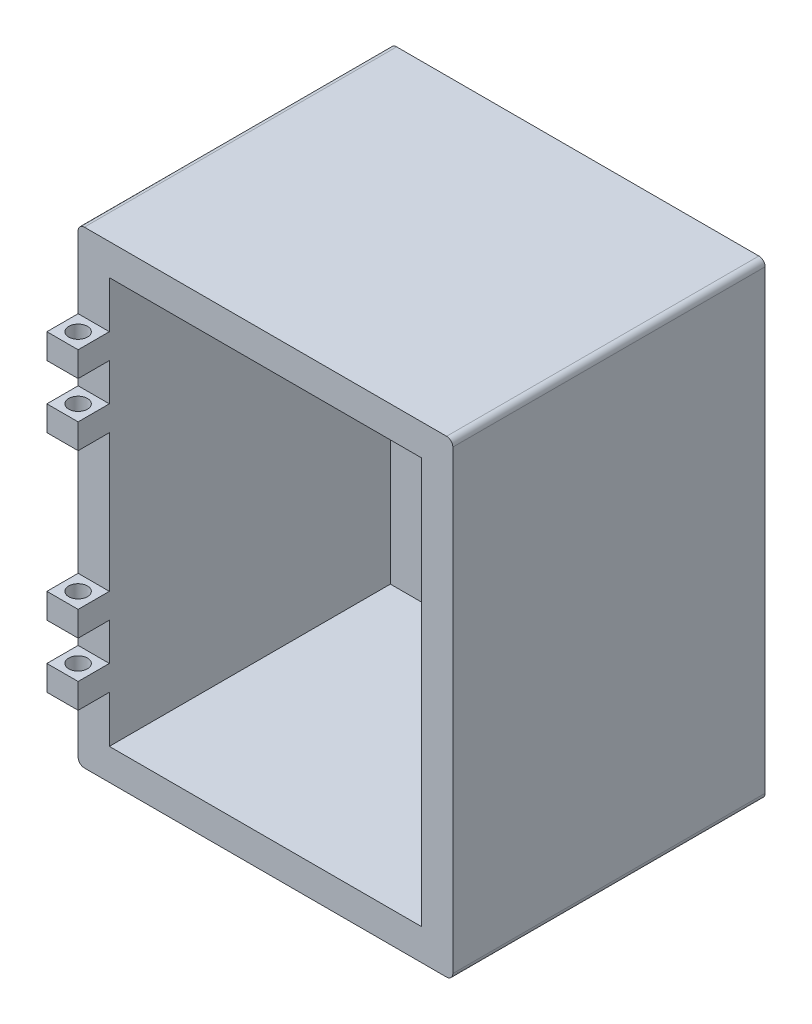
SolidWorks part; units mm, degrees
ref_plane "Front Plane" through (0, 0, 0) normal (0, 0, 1) x (1, 0, 0)
ref_plane "Top Plane" through (0, 0, 0) normal (0, 1, 0) x (1, 0, 0)
ref_plane "Right Plane" through (0, 0, 0) normal (1, 0, 0) x (0, 0, -1)
sketch "Sketch1" plane through (0, 0, 0) normal (0, 0, 1) x (1, 0, 0)
  line L1 (0, 0) -> (120, 0)
  line L2 (0, 0) -> (0, 150)
  line L3 (0, 150) -> (120, 150)
  line L4 (120, 0) -> (120, 150)
  dimension "D1" = 120
  dimension "D2" = 150
extrude "Boss-Extrude1" add sketch "Sketch1" along normal blind 100
shell "Shell1" thickness 10
sketch "Sketch2" plane through (0, 0, 100) normal (0, 0, 1) x (1, 0, 0)
  line L0 (0, 150) -> (0, 0) construction
  line L1 (0, 97) -> (10, 97)
  line L2 (0, 97) -> (0, 105)
  line L3 (0, 105) -> (10, 105)
  line L4 (10, 97) -> (10, 105)
  line L5 (10, 140) -> (10, 10) construction
  line L6 (0, 117) -> (10, 117)
  line L7 (0, 117) -> (0, 125)
  line L8 (0, 125) -> (10, 125)
  line L9 (10, 117) -> (10, 125)
  line L10 (10, 75) -> (-10.1587, 75) construction
  line L11 (10, 33) -> (10, 25)
  line L12 (0, 25) -> (10, 25)
  line L13 (0, 33) -> (0, 25)
  line L14 (0, 33) -> (10, 33)
  line L15 (10, 53) -> (10, 45)
  line L16 (0, 45) -> (10, 45)
  line L17 (0, 53) -> (0, 45)
  line L18 (0, 53) -> (10, 53)
  dimension "D1" = 8
  dimension "D2" = 12
  dimension "D3" = 22
extrude "Boss-Extrude2" add sketch "Sketch2" along normal blind 10
sketch "Sketch3" plane through (0, 125, 0) normal (0, 1, 0) x (1, 0, 0)
  line L0 (10, -110) -> (0, -110) construction
  line L1 (0, -110) -> (0, -100) construction
  circle A0 centre (5, -105) radius 3
  dimension "D1" = 6
  dimension "D2" = 5
  dimension "D3" = 5
extrude "Cut-Extrude1" cut sketch "Sketch3" against normal through all
fillet "Fillet1" radius 2 4 edges at (120, 0, 50) (0, 0, 50) (120, 150, 50) (0, 150, 50)
